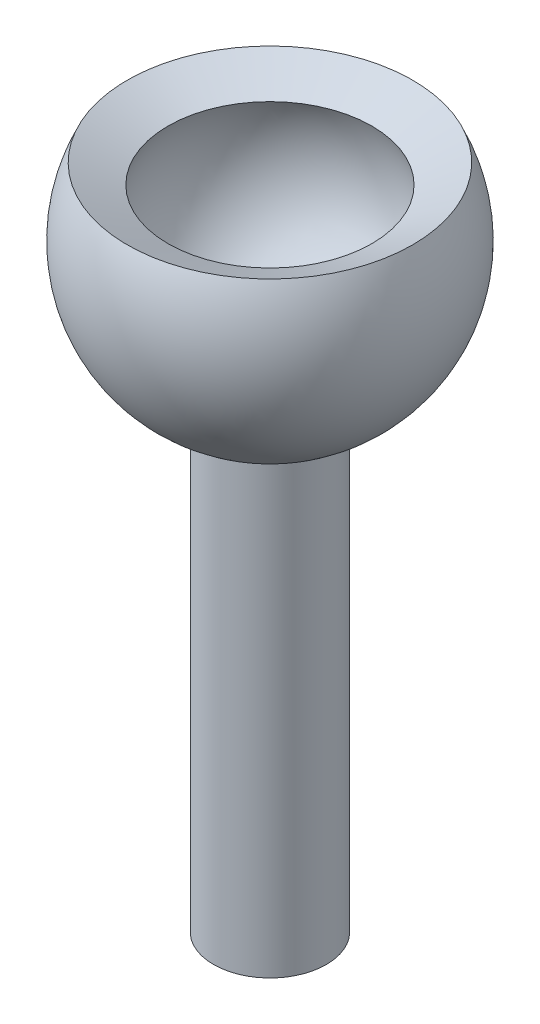
SolidWorks part; units mm, degrees
ref_plane "Front" through (0, 0, 0) normal (0, 0, 1) x (1, 0, 0)
ref_plane "Top" through (0, 0, 0) normal (0, 1, 0) x (1, 0, 0)
ref_plane "Right" through (0, 0, 0) normal (1, 0, 0) x (0, 0, -1)
sketch "Sketch1" plane through (0, 0, 0) normal (0, 0, 1) x (1, 0, 0)
  line L0 (2.5, -6.5383) -> (2.5, -26.5383)
  line L3 (4.5175, 2.1429) -> (6.3246, 3)
  line L4 (0, 12.863) -> (0, -43.0612) construction
  line L5 (2.5, -26.5383) -> (0, -26.5383)
  line L6 (0.5, -4.9749) -> (0.5, -26.5383) construction
  line L7 (0, -26.5383) -> (0, -5)
  arc A0 (6.3246, 3) -> (2.5, -6.5383) centre (0, 0) cw
  arc A1 (4.5175, 2.1429) -> (0, -5) centre (0, 0) cw
  arc A2 (4.5175, 2.1429) -> (0.5, -4.9749) centre (0, 0) cw construction
  dimension "D4" = 5
  dimension "D2" = 20
  dimension "D3" = 3
  dimension "D5" = 2.5
  dimension "D1" = 2
revolve "Revolve1" add sketch "Sketch1" angle 360 about L4
